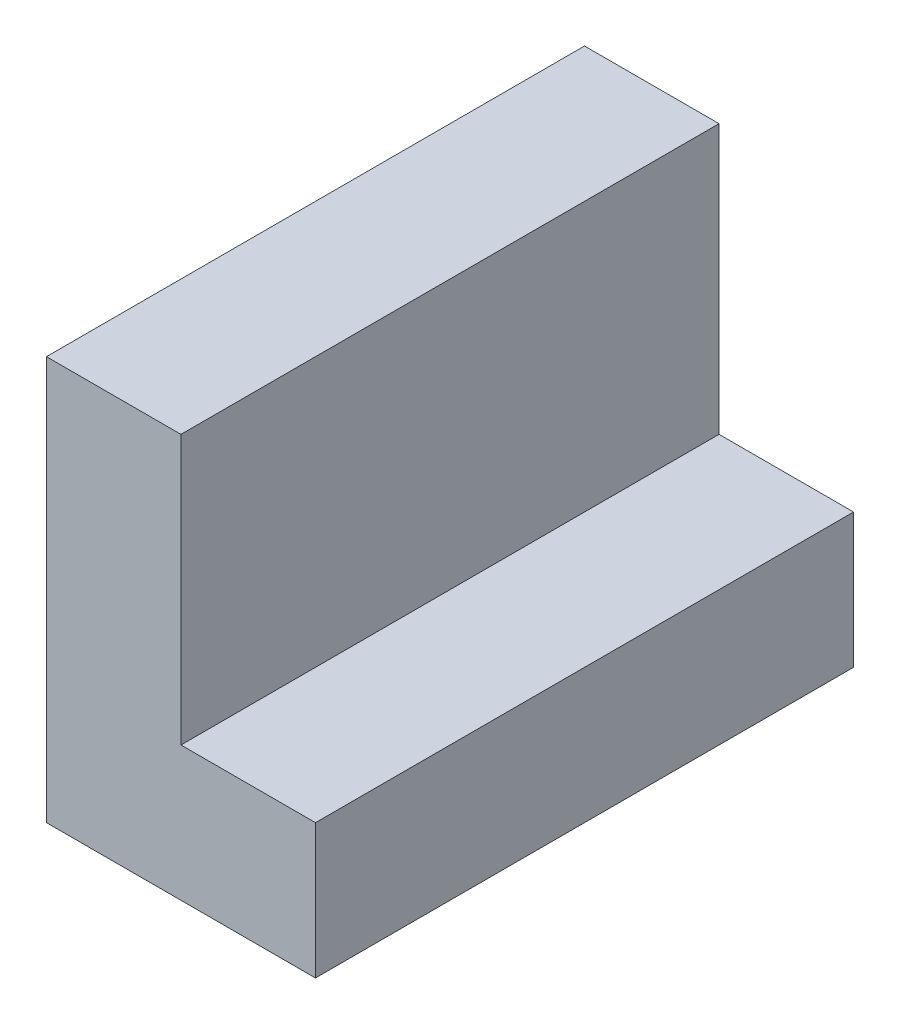
SolidWorks part; units mm, degrees
ref_plane "Alzado" through (0, 0, 0) normal (0, 0, 1) x (1, 0, 0)
ref_plane "Planta" through (0, 0, 0) normal (0, 1, 0) x (1, 0, 0)
ref_plane "Vista lateral" through (0, 0, 0) normal (1, 0, 0) x (0, 0, -1)
sketch "Croquis1" plane through (0, 0, 0) normal (0, 0, 1) x (1, 0, 0)
  line L0 (0, 0) -> (20, 0)
  line L1 (20, 0) -> (20, 10)
  line L2 (20, 10) -> (10, 10)
  line L3 (10, 10) -> (10, 30)
  line L4 (10, 30) -> (0, 30)
  line L5 (0, 30) -> (0, 0)
  dimension "D1" = 10
  dimension "D2" = 20
  dimension "D3" = 30
extrude "L block" add sketch "Croquis1" along normal blind 40
